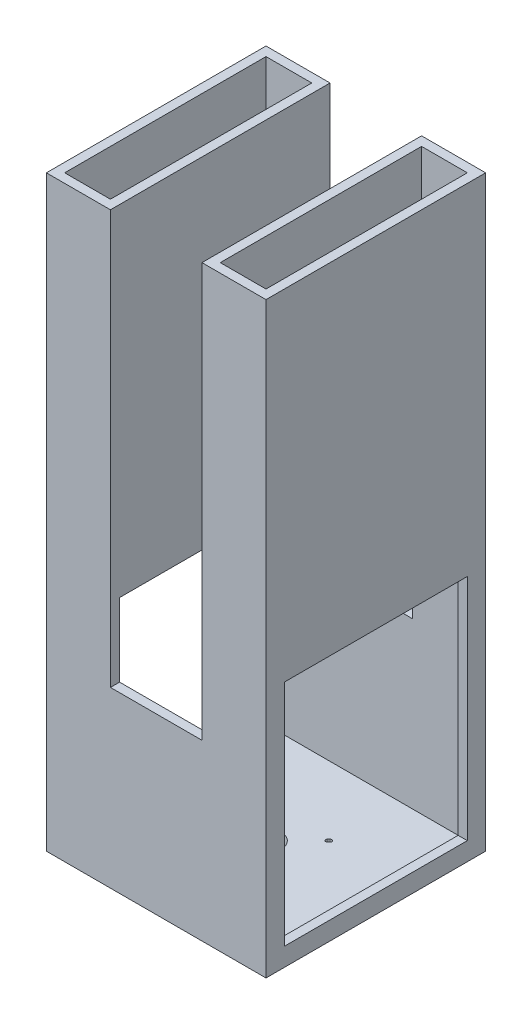
SolidWorks part; units mm, degrees
ref_plane "Front Plane" through (0, 0, 0) normal (0, 0, 1) x (1, 0, 0)
ref_plane "Top Plane" through (0, 0, 0) normal (0, 1, 0) x (1, 0, 0)
ref_plane "Right Plane" through (0, 0, 0) normal (1, 0, 0) x (0, 0, -1)
sketch "Sketch1" plane through (0, 0, 0) normal (0, 1, 0) x (1, 0, 0)
  line L1 (120, -120) -> (-120, -120)
  line L2 (120, -120) -> (120, 120)
  line L3 (120, 120) -> (-120, 120)
  line L4 (-120, -120) -> (-120, 120)
  line L5 (120, -120) -> (-120, 120) construction
  line L6 (120, 120) -> (-120, -120) construction
  line L7 (110, -110) -> (-110, -110)
  line L8 (110, -110) -> (110, 110)
  line L9 (110, 110) -> (-110, 110)
  line L10 (-110, -110) -> (-110, 110)
  line L11 (110, -110) -> (-110, 110) construction
  line L12 (110, 110) -> (-110, -110) construction
  point P0 (0, 0)
  point P6 (0, 0)
  dimension "D1" = 240
  dimension "D2" = 240
  dimension "D3" = 10
  dimension "D4" = 10
extrude "Boss-Extrude1" add sketch "Sketch1" along normal blind 260
sketch "Sketch2" plane through (0, 0, 0) normal (0, -1, 0) x (1, 0, 0)
  line L0 (-120, 120) -> (120, 120) construction
  line L1 (120, -120) -> (-120, -120)
  line L2 (120, -120) -> (120, 120)
  line L3 (120, 120) -> (-120, 120)
  line L4 (-120, -120) -> (-120, 120)
  line L5 (120, -120) -> (-120, 120) construction
  line L6 (120, 120) -> (-120, -120) construction
  line L9 (-120, -120) -> (-120, 120) construction
  point P0 (0, 0)
extrude "Boss-Extrude2" add sketch "Sketch2" along normal blind 10
sketch "Sketch3" plane through (0, -10, 0) normal (0, -1, 0) x (1, 0, 0)
  circle A0 centre (0, 0) radius 16.5
  dimension "D1" = 33
extrude "Cut-Extrude1" cut sketch "Sketch3" against normal blind 20
sketch "Sketch7" plane through (0, -10, 0) normal (0, -1, 0) x (-1, 0, 0)
  line L8 (-36.416, 33.5876) -> (-35.0018, 32.1734)
  line L9 (-33.5876, 36.416) -> (-32.1734, 35.0018)
  line L10 (32.1734, 35.0018) -> (33.5876, 36.416)
  line L11 (35.0018, 32.1734) -> (36.416, 33.5876)
  line L12 (35.0018, -32.1734) -> (36.416, -33.5876)
  line L13 (32.1734, -35.0018) -> (33.5876, -36.416)
  line L14 (-36.416, -33.5876) -> (-35.0018, -32.1734)
  line L15 (-33.5876, -36.416) -> (-32.1734, -35.0018)
  line L16 (0, -14.54) -> (0, 14.54) construction
  line L18 (0, 0) -> (-67.1751, 67.1751) construction
  line L19 (0, 0) -> (67.1751, 67.1751) construction
  arc A8 (36.416, 33.5876) -> (33.5876, 36.416) centre (35.0018, 35.0018) ccw
  arc A9 (32.1734, 35.0018) -> (35.0018, 32.1734) centre (33.5876, 33.5876) ccw
  arc A10 (-33.5876, 36.416) -> (-36.416, 33.5876) centre (-35.0018, 35.0018) ccw
  arc A11 (-35.0018, 32.1734) -> (-32.1734, 35.0018) centre (-33.5876, 33.5876) ccw
  arc A12 (-36.416, -33.5876) -> (-33.5876, -36.416) centre (-35.0018, -35.0018) ccw
  arc A13 (-32.1734, -35.0018) -> (-35.0018, -32.1734) centre (-33.5876, -33.5876) ccw
  arc A14 (33.5876, -36.416) -> (36.416, -33.5876) centre (35.0018, -35.0018) ccw
  arc A15 (35.0018, -32.1734) -> (32.1734, -35.0018) centre (33.5876, -33.5876) ccw
  dimension "D1" = 4
  dimension "D2" = 47.5
  dimension "D3" = 47.5
  dimension "D4" = 45
  dimension "D5" = 45
  dimension "D6" = 45
  dimension "D7" = 45
  dimension "D8" = 47.5
  dimension "D9" = 47.5
extrude "Cut-Extrude3" cut sketch "Sketch7" against normal blind 10
sketch "Sketch8" plane through (0, 0, 120) normal (0, 0, 1) x (1, 0, 0)
  line L1 (-50, 288.813) -> (50, 288.813)
  line L2 (-50, 288.813) -> (-50, 180)
  line L3 (-50, 180) -> (50, 180)
  line L4 (50, 288.813) -> (50, 180)
  line L5 (-50, 288.813) -> (50, 180) construction
  line L6 (-50, 180) -> (50, 288.813) construction
  line L8 (120, 260) -> (120, -10) construction
  line L9 (-120, 260) -> (120, 260) construction
  line L10 (-120, 260) -> (-120, -10) construction
  point P0 (0, 234.4065)
  dimension "D1" = 70
  dimension "D2" = 80
  dimension "D3" = 70
extrude "Cut-Extrude4" cut sketch "Sketch8" against normal blind 296
sketch "Sketch9" plane through (0, 260, 0) normal (0, 1, 0) x (1, 0, 0)
  line L0 (-50, 110) -> (-50, 120)
  line L1 (-50, 120) -> (-120, 120)
  line L2 (-120, 120) -> (-120, -120)
  line L3 (-120, -120) -> (-50, -120)
  line L4 (-50, -120) -> (-50, -110)
  line L5 (-110, -110) -> (110, -110) construction
  line L6 (-110, -110) -> (-50, -110) construction
  line L7 (-50, -110) -> (-110, -110)
  line L8 (-110, -110) -> (-110, 110)
  line L9 (-110, 110) -> (-50, 110)
  line L10 (50, 110) -> (50, 120)
  line L11 (50, 120) -> (120, 120)
  line L12 (120, 120) -> (120, -120)
  line L13 (120, -120) -> (50, -120)
  line L14 (50, -120) -> (50, -110)
  line L15 (50, -110) -> (110, -110)
  line L16 (110, -110) -> (110, 110)
  line L17 (110, 110) -> (50, 110)
extrude "Boss-Extrude4" add sketch "Sketch9" along normal blind 372
sketch "Sketch10" plane through (120, 0, 0) normal (1, 0, 0) x (0, 0, -1)
  line L0 (120, -10) -> (-120, -10) construction
  line L1 (100, 10) -> (-100, 10)
  line L2 (100, 10) -> (100, 260)
  line L3 (100, 260) -> (-100, 260)
  line L4 (-100, 10) -> (-100, 260)
  line L5 (100, 10) -> (-100, 260) construction
  line L6 (100, 260) -> (-100, 10) construction
  line L7 (-120, 632) -> (-120, -10) construction
  line L8 (120, 632) -> (120, -10) construction
  point P0 (0, 135)
  dimension "D1" = 20
  dimension "D2" = 20
  dimension "D3" = 20
  dimension "D4" = 250
extrude "Cut-Extrude5" cut sketch "Sketch10" against normal blind 372
sketch "Sketch11" plane through (0, 632, 0) normal (0, 1, 0) x (1, 0, 0)
  line L0 (50, 110) -> (50, -110)
  line L1 (50, -110) -> (60, -110)
  line L2 (-110, -110) -> (110, -110) construction
  line L3 (60, -110) -> (60, 110)
  line L4 (50, 110) -> (110, 110) construction
  line L5 (60, 110) -> (50, 110)
  line L6 (-50, 110) -> (-50, -110)
  line L7 (-50, -110) -> (-60, -110)
  line L8 (-50, -110) -> (-110, -110) construction
  line L9 (-60, -110) -> (-60, 110)
  line L10 (-110, 110) -> (-50, 110) construction
  line L11 (-60, 110) -> (-50, 110)
  dimension "D1" = 10
  dimension "D2" = 10
extrude "Boss-Extrude6" add sketch "Sketch11" against normal blind 362
sketch "Sketch12" plane through (0, 270, 0) normal (0, -1, 0) x (1, 0, 0)
  line L0 (50, -120) -> (50, 120) construction
  line L1 (-50, 120) -> (-120, 120)
  line L2 (-50, 120) -> (-50, -120)
  line L3 (-50, -120) -> (-120, -120)
  line L4 (-120, 120) -> (-120, -120)
  line L5 (-50, 120) -> (-120, -120) construction
  line L6 (-50, -120) -> (-120, 120) construction
  line L7 (50, 120) -> (120, 120)
  line L8 (50, 120) -> (50, -120)
  line L9 (50, -120) -> (120, -120)
  line L10 (120, 120) -> (120, -120)
  line L11 (50, 120) -> (120, -120) construction
  line L12 (50, -120) -> (120, 120) construction
  line L13 (-50, 120) -> (-50, -120) construction
  line L14 (-120, 120) -> (-50, 120) construction
  line L15 (50, 120) -> (120, 120) construction
  point P0 (-85, 0)
  point P6 (85, 0)
extrude "Boss-Extrude7" add sketch "Sketch12" along normal blind 10
